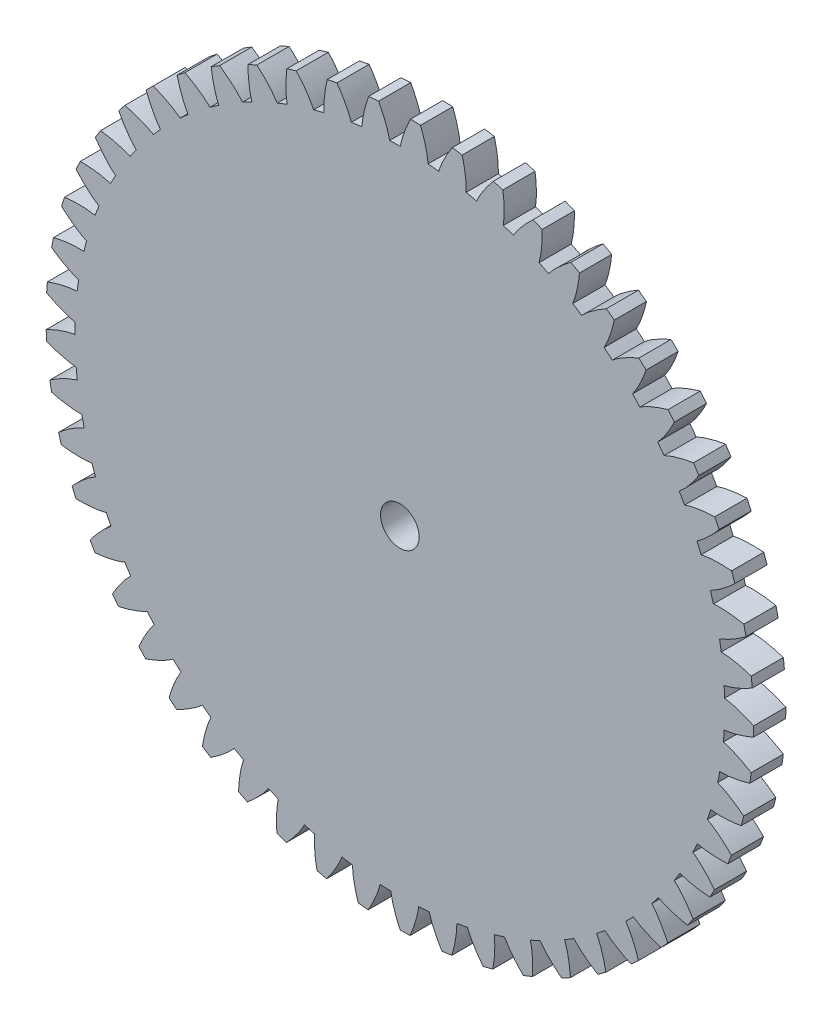
SolidWorks part; units mm, degrees
ref_plane "前视基准面" through (0, 0, 0) normal (0, 0, 1) x (1, 0, 0)
ref_plane "上视基准面" through (0, 0, 0) normal (0, 1, 0) x (1, 0, 0)
ref_plane "右视基准面" through (0, 0, 0) normal (1, 0, 0) x (0, 0, -1)
other "Configuration Table"
sketch "草图1" plane through (0, 0, 0) normal (0, 0, 1) x (1, 0, 0)
  line L0 (0, -0.6254) -> (0.7899, 52.9941) construction
  line L1 (0, 0) -> (2.4394, 54.9459) construction
  line L2 (0, 0) -> (5.6902, 54.7049) construction
  circle A1 centre (0, 0) radius 50.5
  circle A2 centre (0, 0) radius 55
  circle A3 centre (0, 0) radius 53
  spline S0 degree 4 poles (0, 49.8037) (0.0009, 49.8441) (0.0062, 49.9572) (0.0271, 50.1706) (0.0767, 50.5172) (0.2017, 51.1568) (0.406, 51.9145) (0.6892, 52.7572) (1.0452, 53.6472) (1.3816, 54.3975) (1.7458, 55.1347) (2.1353, 55.8588) (2.636, 56.7216) (3.2802, 57.738) (4.0884, 58.8925) (5.0797, 60.1668) (6.1512, 61.415) (7.277, 62.6131) (8.307, 63.6193) (9.2162, 64.4504) (9.9947, 65.1248) (10.6222, 65.6491) (11.4311, 66.297) (12.2339, 66.9127) (13.0864, 67.5292) (14.0681, 68.2126) (14.984, 68.8118) (15.7557, 69.3016) (16.7458, 69.8914) (17.2547, 70.186) (17.9782, 70.5929) (18.5198, 70.8852) (19.0141, 71.1478) (19.2931, 71.2903) (19.4555, 71.3741) knots 0 0 0 0 0 0.005377 0.015084 0.028532 0.04661 0.092111 0.119476 0.146842 0.174209 0.201575 0.228941 0.256307 0.307035 0.361767 0.4165 0.471232 0.525964 0.580697 0.608063 0.635429 0.662795 0.690161 0.744894 0.77226 0.799626 0.854358 0.881725 0.909091 0.931818 0.954545 0.977273 1 1 1 1 1 construction
  spline S1 degree 4 poles (0.0782, 50.4999) (0.0847, 50.5384) (0.1149, 50.7105) (0.2179, 51.2167) (0.406, 51.9145) (0.6892, 52.7572) (1.067, 53.7016) (1.3456, 54.3168) (1.5514, 54.739) (1.6707, 54.9746) knots 0.023342 0.023342 0.023342 0.023342 0.023342 0.028532 0.04661 0.092111 0.119476 0.146842 0.182011 0.182011 0.182011 0.182011 0.182011
  spline S2 degree 4 poles (4.3974, 50.3082) (4.3943, 50.347) (4.3795, 50.5211) (4.3218, 51.0345) (4.1963, 51.7462) (3.9888, 52.6107) (3.6962, 53.5849) (3.4732, 54.2223) (3.3057, 54.6611) (3.2077, 54.9064) knots 0.023342 0.023342 0.023342 0.023342 0.023342 0.028532 0.04661 0.092111 0.119476 0.146842 0.182011 0.182011 0.182011 0.182011 0.182011
  spline S3 degree 4 poles (6.0504, 50.1362) (6.0614, 50.1736) (6.1118, 50.3409) (6.2739, 50.8315) (6.5432, 51.5021) (6.9242, 52.3054) (7.411, 53.1985) (7.7604, 53.7764) (8.0147, 54.1713) (8.161, 54.3912) knots 0.023342 0.023342 0.023342 0.023342 0.023342 0.028532 0.04661 0.092111 0.119476 0.146842 0.182011 0.182011 0.182011 0.182011 0.182011
  dimension "D1" = 106
  dimension "D2" = 101
  dimension "D3" = 110
  dimension "D4" = 1.698
  dimension "D5" = 5.094
sketch "草图2" plane through (0, 0, 0) normal (0, 0, 1) x (1, 0, 0)
  circle A0 centre (0, 0) radius 50.5 construction
  circle A1 centre (0, 0) radius 55 construction
  arc A2 (6.0504, 50.1362) -> (4.3974, 50.3082) centre (0, 0) ccw
  arc A3 (3.2077, 54.9064) -> (1.6707, 54.9746) centre (0, 0) ccw
  arc A4 (9.6792, 54.1416) -> (8.161, 54.3912) centre (0, 0) ccw
  arc A5 (11.9377, 49.0687) -> (10.3166, 49.435) centre (0, 0) ccw
  arc A6 (16.0147, 52.6168) -> (14.5367, 53.0442) centre (0, 0) ccw
  arc A7 (17.6575, 47.3124) -> (16.0911, 47.8678) centre (0, 0) ccw
  arc A8 (22.1255, 50.3534) -> (20.7084, 50.9526) centre (0, 0) ccw
  arc A9 (23.1293, 44.8919) -> (21.6396, 45.6287) centre (0, 0) ccw
  arc A10 (27.9256, 47.3831) -> (26.5894, 48.1457) centre (0, 0) ccw
  arc A11 (28.2765, 41.8412) -> (26.8844, 42.749) centre (0, 0) ccw
  arc A12 (33.3338, 43.7477) -> (32.0971, 44.6629) centre (0, 0) ccw
  arc A13 (33.0267, 38.2032) -> (31.7517, 39.2693) centre (0, 0) ccw
  arc A14 (38.274, 39.4981) -> (37.1542, 40.5532) centre (0, 0) ccw
  arc A15 (37.3133, 34.0289) -> (36.1734, 35.2383) centre (0, 0) ccw
  arc A16 (42.6769, 34.6941) -> (41.6898, 35.8742) centre (0, 0) ccw
  arc A17 (41.0761, 29.3769) -> (40.0872, 30.7126) centre (0, 0) ccw
  arc A18 (46.4808, 29.4031) -> (45.6401, 30.6917) centre (0, 0) ccw
  arc A19 (44.2623, 24.3125) -> (43.4383, 25.7558) centre (0, 0) ccw
  arc A20 (49.6321, 23.6992) -> (48.9498, 25.0782) centre (0, 0) ccw
  arc A21 (46.8272, 18.9068) -> (46.1797, 20.4374) centre (0, 0) ccw
  arc A22 (52.0867, 17.6628) -> (51.5723, 19.1128) centre (0, 0) ccw
  arc A23 (48.7347, 13.2357) -> (48.2727, 14.8322) centre (0, 0) ccw
  arc A24 (53.8102, 11.3783) -> (53.4708, 12.879) centre (0, 0) ccw
  arc A25 (49.958, 7.3788) -> (49.6882, 9.0187) centre (0, 0) ccw
  arc A26 (54.7782, 4.9342) -> (54.6188, 6.4644) centre (0, 0) ccw
  arc A27 (50.4801, 1.4183) -> (50.4061, 3.0786) centre (0, 0) ccw
  arc A28 (54.9773, -1.5793) -> (55, -0.0409) centre (0, 0) ccw
  arc A29 (50.2935, -4.5621) -> (50.4164, -2.9047) centre (0, 0) ccw
  arc A30 (54.4047, -8.0705) -> (54.6091, -6.5456) centre (0, 0) ccw
  arc A31 (49.4009, -10.4784) -> (49.719, -8.8472) centre (0, 0) ccw
  arc A32 (53.0683, -14.4485) -> (53.4516, -12.9585) centre (0, 0) ccw
  arc A33 (47.8149, -16.2477) -> (48.3236, -14.6655) centre (0, 0) ccw
  arc A34 (50.9869, -20.6236) -> (51.5438, -19.1894) centre (0, 0) ccw
  arc A35 (45.5576, -21.7889) -> (46.2499, -20.278) centre (0, 0) ccw
  arc A36 (48.1898, -26.5093) -> (48.9125, -25.151) centre (0, 0) ccw
  arc A37 (42.6608, -27.0242) -> (43.5269, -25.6058) centre (0, 0) ccw
  arc A38 (44.7163, -32.0228) -> (45.5945, -30.7595) centre (0, 0) ccw
  arc A39 (39.1651, -31.8801) -> (40.193, -30.5741) centre (0, 0) ccw
  arc A40 (40.615, -37.0867) -> (41.6364, -35.9362) centre (0, 0) ccw
  arc A41 (35.1197, -36.2885) -> (36.2948, -35.1133) centre (0, 0) ccw
  arc A42 (35.9435, -41.6301) -> (37.0939, -40.6084) centre (0, 0) ccw
  arc A43 (30.5812, -40.1876) -> (31.887, -39.1595) centre (0, 0) ccw
  arc A44 (30.7675, -45.589) -> (32.0307, -44.7106) centre (0, 0) ccw
  arc A45 (25.6135, -43.5224) -> (27.0317, -42.656) centre (0, 0) ccw
  arc A46 (25.1596, -48.908) -> (26.5178, -48.1851) centre (0, 0) ccw
  arc A47 (20.2861, -46.2463) -> (21.7969, -45.5538) centre (0, 0) ccw
  arc A48 (19.1985, -51.5404) -> (20.6326, -50.9833) centre (0, 0) ccw
  arc A49 (14.6741, -48.321) -> (16.2561, -47.812) centre (0, 0) ccw
  arc A50 (12.9679, -53.4494) -> (14.4579, -53.0657) centre (0, 0) ccw
  arc A51 (8.856, -49.7174) -> (10.4872, -49.3991) centre (0, 0) ccw
  arc A52 (6.5553, -54.608) -> (8.0801, -54.4032) centre (0, 0) ccw
  arc A53 (2.9136, -50.4159) -> (4.571, -50.2927) centre (0, 0) ccw
  arc A54 (0.0506, -55) -> (1.589, -54.977) centre (0, 0) ccw
  arc A55 (-3.0697, -50.4066) -> (-1.4094, -50.4803) centre (0, 0) ccw
  arc A56 (-6.4548, -54.6199) -> (-4.9245, -54.7791) centre (0, 0) ccw
  arc A57 (-9.0099, -49.6898) -> (-7.37, -49.9593) centre (0, 0) ccw
  arc A58 (-12.8696, -53.4731) -> (-11.3688, -53.8122) centre (0, 0) ccw
  arc A59 (-14.8236, -48.2754) -> (-13.2271, -48.737) centre (0, 0) ccw
  arc A60 (-19.1037, -51.5757) -> (-17.6536, -52.0898) centre (0, 0) ccw
  arc A61 (-20.4293, -46.1833) -> (-18.8985, -46.8305) centre (0, 0) ccw
  arc A62 (-25.0696, -48.9542) -> (-23.6905, -49.6363) centre (0, 0) ccw
  arc A63 (-25.7481, -43.4429) -> (-24.3047, -44.2666) centre (0, 0) ccw
  arc A64 (-30.6836, -45.6456) -> (-29.3948, -46.4859) centre (0, 0) ccw
  arc A65 (-30.7055, -40.0926) -> (-29.3696, -41.0813) centre (0, 0) ccw
  arc A66 (-35.8669, -41.6961) -> (-34.6866, -42.683) centre (0, 0) ccw
  arc A67 (-35.2319, -36.1796) -> (-34.0223, -37.3193) centre (0, 0) ccw
  arc A68 (-40.5467, -37.1614) -> (-39.4914, -38.281) centre (0, 0) ccw
  arc A69 (-39.2637, -31.7587) -> (-38.1974, -33.0335) centre (0, 0) ccw
  arc A70 (-44.6573, -32.105) -> (-43.7418, -33.3415) centre (0, 0) ccw
  arc A71 (-42.7443, -26.8919) -> (-41.8363, -28.2839) centre (0, 0) ccw
  arc A72 (-48.141, -26.5979) -> (-47.3782, -27.934) centre (0, 0) ccw
  arc A73 (-45.6249, -21.6477) -> (-44.8878, -23.1373) centre (0, 0) ccw
  arc A74 (-50.9489, -20.7174) -> (-50.3495, -22.1344) centre (0, 0) ccw
  arc A75 (-47.865, -16.0995) -> (-47.3093, -17.6658) centre (0, 0) ccw
  arc A76 (-53.0416, -14.5461) -> (-52.614, -16.024) centre (0, 0) ccw
  arc A77 (-49.4332, -10.3254) -> (-49.0666, -11.9464) centre (0, 0) ccw
  arc A78 (-54.3897, -8.1706) -> (-54.1399, -9.6887) centre (0, 0) ccw
  arc A79 (-50.3074, -4.4063) -> (-50.1352, -6.0593) centre (0, 0) ccw
  arc A80 (-54.9743, -1.6804) -> (-54.9058, -3.2174) centre (0, 0) ccw
  arc A81 (-50.4754, 1.5747) -> (-50.4999, -0.0871) centre (0, 0) ccw
  arc A82 (-54.7872, 4.8334) -> (-54.901, 3.299) centre (0, 0) ccw
  arc A83 (-49.9349, 7.5335) -> (-50.1558, 5.8863) centre (0, 0) ccw
  arc A84 (-53.831, 11.2793) -> (-54.1254, 9.7692) centre (0, 0) ccw
  arc A85 (-48.6934, 13.3866) -> (-49.1075, 11.777) centre (0, 0) ccw
  arc A86 (-52.1191, 17.5669) -> (-52.5901, 16.1022) centre (0, 0) ccw
  arc A87 (-46.7684, 19.0517) -> (-47.37, 17.5025) centre (0, 0) ccw
  arc A88 (-49.6756, 23.6079) -> (-50.3165, 22.2092) centre (0, 0) ccw
  arc A89 (-44.1868, 24.4495) -> (-44.9674, 22.9822) centre (0, 0) ccw
  arc A90 (-46.5348, 29.3175) -> (-47.3366, 28.0044) centre (0, 0) ccw
  arc A91 (-40.9849, 29.504) -> (-41.9336, 28.1394) centre (0, 0) ccw
  arc A92 (-42.7407, 34.6155) -> (-43.6922, 33.4065) centre (0, 0) ccw
  arc A93 (-37.2077, 34.1443) -> (-38.3111, 32.9015) centre (0, 0) ccw
  arc A94 (-38.3466, 39.4276) -> (-39.4344, 38.3396) centre (0, 0) ccw
  arc A95 (-32.9082, 38.3053) -> (-34.1509, 37.2017) centre (0, 0) ccw
  arc A96 (-33.4142, 43.6863) -> (-34.6231, 42.7346) centre (0, 0) ccw
  arc A97 (-28.1468, 41.9286) -> (-29.5112, 40.9797) centre (0, 0) ccw
  arc A98 (-28.0128, 47.3317) -> (-29.3257, 46.5296) centre (0, 0) ccw
  arc A99 (-22.9902, 44.9633) -> (-24.4573, 44.1825) centre (0, 0) ccw
  arc A100 (-22.2181, 50.3126) -> (-23.6167, 49.6714) centre (0, 0) ccw
  arc A101 (-17.5108, 47.3669) -> (-19.06, 46.765) centre (0, 0) ccw
  arc A102 (-16.1115, 52.5873) -> (-17.5761, 52.116) centre (0, 0) ccw
  arc A103 (-11.7857, 49.1055) -> (-13.3952, 48.6911) centre (0, 0) ccw
  arc A104 (-9.7788, 54.1237) -> (-11.2888, 53.829) centre (0, 0) ccw
  arc A105 (-5.8951, 50.1547) -> (-7.5423, 49.9336) centre (0, 0) ccw
  arc A106 (-3.3087, 54.9004) -> (-4.8431, 54.7864) centre (0, 0) ccw
  arc A107 (0.0782, 50.4999) -> (-1.5836, 50.4752) centre (0, 0) ccw
  spline S1 degree 4 poles (-2987.0139, 269.4484) (-118.9779, 32.2173) (-1.5624, 33.5542) (5.7155, 43.1306) (4.1963, 51.7462) (3.9888, 52.6107) (-3.1358, 76.3332) (-47.8281, 87.469) (81.7258, 73.9843) (-2995.7873, -8.3312) knots -1.04429 -1.04429 -1.04429 -1.04429 -1.04429 0.028532 0.04661 0.092111 0.119476 0.146842 3.343823 3.343823 3.343823 3.343823 3.343823 only from (4.3974, 50.3082) to (3.2077, 54.9064) construction
  spline S2 degree 4 poles (2999.1401, 3.6794) (121.3648, 21.5467) (4.5298, 33.2837) (-1.8708, 43.4674) (0.406, 51.9145) (0.6892, 52.7572) (9.8881, 75.755) (55.3914, 82.8863) (-74.8477, 80.9358) (2983.2621, -273.7849) knots -1.04429 -1.04429 -1.04429 -1.04429 -1.04429 0.028532 0.04661 0.092111 0.119476 0.146842 3.343823 3.343823 3.343823 3.343823 3.343823 only from (0.0782, 50.4999) to (1.6707, 54.9746) construction
  spline S3 degree 4 poles (6.0504, 50.1362) (6.0614, 50.1736) (6.1118, 50.3409) (6.2739, 50.8315) (6.5432, 51.5021) (6.9242, 52.3054) (7.411, 53.1985) (7.7604, 53.7764) (8.0147, 54.1713) (8.161, 54.3912) knots 0.023342 0.023342 0.023342 0.023342 0.023342 0.028532 0.04661 0.092111 0.119476 0.146842 0.182011 0.182011 0.182011 0.182011 0.182011
  spline S4 degree 4 poles (4.3974, 50.3082) (4.3943, 50.347) (4.3795, 50.5211) (4.3218, 51.0345) (4.1963, 51.7462) (3.9888, 52.6107) (3.6962, 53.5849) (3.4732, 54.2223) (3.3057, 54.6611) (3.2077, 54.9064) knots 0.023342 0.023342 0.023342 0.023342 0.023342 0.028532 0.04661 0.092111 0.119476 0.146842 0.182011 0.182011 0.182011 0.182011 0.182011
  spline S5 degree 4 poles (0.0782, 50.4999) (0.0847, 50.5384) (0.1149, 50.7105) (0.2179, 51.2167) (0.406, 51.9145) (0.6892, 52.7572) (1.067, 53.7016) (1.3456, 54.3168) (1.5514, 54.739) (1.6707, 54.9746) knots 0.023342 0.023342 0.023342 0.023342 0.023342 0.028532 0.04661 0.092111 0.119476 0.146842 0.182011 0.182011 0.182011 0.182011 0.182011
  spline S6 degree 4 poles (10.3166, 49.435) (10.3182, 49.4739) (10.324, 49.6486) (10.3275, 50.1651) (10.287, 50.8867) (10.1833, 51.7697) (10.008, 52.7716) (9.8619, 53.431) (9.7474, 53.8865) (9.6792, 54.1416) knots 0.023342 0.023342 0.023342 0.023342 0.023342 0.028532 0.04661 0.092111 0.119476 0.146842 0.182011 0.182011 0.182011 0.182011 0.182011
  spline S7 degree 4 poles (11.9377, 49.0687) (11.9531, 49.1046) (12.0229, 49.2647) (12.2419, 49.7326) (12.5886, 50.3667) (13.0619, 51.1193) (13.6509, 51.9486) (14.0663, 52.4811) (14.3654, 52.8431) (14.5367, 53.0442) knots 0.023342 0.023342 0.023342 0.023342 0.023342 0.028532 0.04661 0.092111 0.119476 0.146842 0.182011 0.182011 0.182011 0.182011 0.182011
  spline S8 degree 4 poles (16.0911, 47.8678) (16.0972, 47.9063) (16.1237, 48.079) (16.1882, 48.5916) (16.2334, 49.3129) (16.2347, 50.2019) (16.1792, 51.2175) (16.1121, 51.8895) (16.0523, 52.3554) (16.0147, 52.6168) knots 0.023342 0.023342 0.023342 0.023342 0.023342 0.028532 0.04661 0.092111 0.119476 0.146842 0.182011 0.182011 0.182011 0.182011 0.182011
  spline S9 degree 4 poles (17.6575, 47.3124) (17.6769, 47.3462) (17.7652, 47.497) (18.038, 47.9357) (18.4573, 48.5243) (19.0163, 49.2157) (19.6992, 49.9694) (20.1746, 50.4491) (20.5145, 50.7732) (20.7084, 50.9526) knots 0.023342 0.023342 0.023342 0.023342 0.023342 0.028532 0.04661 0.092111 0.119476 0.146842 0.182011 0.182011 0.182011 0.182011 0.182011
  spline S10 degree 4 poles (21.6396, 45.6287) (21.6503, 45.6662) (21.697, 45.8346) (21.8216, 46.3359) (21.9518, 47.0468) (22.0583, 47.9294) (22.1233, 48.9445) (22.1361, 49.6197) (22.1319, 50.0894) (22.1255, 50.3534) knots 0.023342 0.023342 0.023342 0.023342 0.023342 0.028532 0.04661 0.092111 0.119476 0.146842 0.182011 0.182011 0.182011 0.182011 0.182011
  spline S11 degree 4 poles (23.1293, 44.8919) (23.1527, 44.9231) (23.2581, 45.0624) (23.5809, 45.4658) (24.0668, 46.0007) (24.7037, 46.6211) (25.471, 47.2888) (25.9998, 47.7088) (26.3756, 47.9905) (26.5894, 48.1457) knots 0.023342 0.023342 0.023342 0.023342 0.023342 0.028532 0.04661 0.092111 0.119476 0.146842 0.182011 0.182011 0.182011 0.182011 0.182011
  spline S12 degree 4 poles (26.8844, 42.749) (26.8994, 42.785) (26.9657, 42.9467) (27.1488, 43.4298) (27.3621, 44.1202) (27.5723, 44.9841) (27.7568, 45.9844) (27.8495, 46.6533) (27.9008, 47.1202) (27.9256, 47.3831) knots 0.023342 0.023342 0.023342 0.023342 0.023342 0.028532 0.04661 0.092111 0.119476 0.146842 0.182011 0.182011 0.182011 0.182011 0.182011
  spline S13 degree 4 poles (28.2765, 41.8412) (28.3034, 41.8695) (28.4246, 41.9953) (28.7928, 42.3577) (29.3386, 42.8314) (30.0443, 43.3721) (30.8852, 43.9444) (31.46, 44.2989) (31.8665, 44.5341) (32.0971, 44.6629) knots 0.023342 0.023342 0.023342 0.023342 0.023342 0.028532 0.04661 0.092111 0.119476 0.146842 0.182011 0.182011 0.182011 0.182011 0.182011
  spline S14 degree 4 poles (31.7517, 39.2693) (31.7709, 39.3032) (31.8558, 39.4559) (32.0948, 39.914) (32.3883, 40.5744) (32.6992, 41.4073) (33.0007, 42.3787) (33.1718, 43.032) (33.278, 43.4895) (33.3338, 43.7477) knots 0.023342 0.023342 0.023342 0.023342 0.023342 0.028532 0.04661 0.092111 0.119476 0.146842 0.182011 0.182011 0.182011 0.182011 0.182011
  spline S15 degree 4 poles (33.0267, 38.2032) (33.0567, 38.2281) (33.192, 38.3387) (33.6005, 38.655) (34.1984, 39.0608) (34.9632, 39.5142) (35.8659, 39.983) (36.4785, 40.2671) (36.91, 40.4526) (37.1542, 40.5532) knots 0.023342 0.023342 0.023342 0.023342 0.023342 0.028532 0.04661 0.092111 0.119476 0.146842 0.182011 0.182011 0.182011 0.182011 0.182011
  spline S16 degree 4 poles (36.1734, 35.2383) (36.1964, 35.2697) (36.2988, 35.4113) (36.5903, 35.8379) (36.9598, 36.4589) (37.367, 37.2492) (37.7813, 38.1782) (38.0285, 38.8066) (38.188, 39.2484) (38.274, 39.4981) knots 0.023342 0.023342 0.023342 0.023342 0.023342 0.028532 0.04661 0.092111 0.119476 0.146842 0.182011 0.182011 0.182011 0.182011 0.182011
  spline S17 degree 4 poles (37.3133, 34.0289) (37.3461, 34.05) (37.4934, 34.1439) (37.9365, 34.4096) (38.5783, 34.7419) (39.3913, 35.1017) (40.343, 35.4604) (40.985, 35.67) (41.4354, 35.8032) (41.6898, 35.8742) knots 0.023342 0.023342 0.023342 0.023342 0.023342 0.028532 0.04661 0.092111 0.119476 0.146842 0.182011 0.182011 0.182011 0.182011 0.182011
  spline S18 degree 4 poles (40.0872, 30.7126) (40.1138, 30.7411) (40.2322, 30.8696) (40.5721, 31.2587) (41.0125, 31.8316) (41.5103, 32.5683) (42.0316, 33.4417) (42.3514, 34.0365) (42.562, 34.4563) (42.6769, 34.6941) knots 0.023342 0.023342 0.023342 0.023342 0.023342 0.028532 0.04661 0.092111 0.119476 0.146842 0.182011 0.182011 0.182011 0.182011 0.182011
  spline S19 degree 4 poles (41.0761, 29.3769) (41.1111, 29.394) (41.2686, 29.4698) (41.7399, 29.6813) (42.4165, 29.9352) (43.2664, 30.1964) (44.2539, 30.44) (44.9162, 30.5722) (45.3792, 30.6512) (45.6401, 30.6917) knots 0.023342 0.023342 0.023342 0.023342 0.023342 0.028532 0.04661 0.092111 0.119476 0.146842 0.182011 0.182011 0.182011 0.182011 0.182011
  spline S20 degree 4 poles (43.4383, 25.7558) (43.4681, 25.7809) (43.6009, 25.8945) (43.9844, 26.2407) (44.4895, 26.7575) (45.0709, 27.4301) (45.6919, 28.2357) (46.0797, 28.7886) (46.3386, 29.1805) (46.4808, 29.4031) knots 0.023342 0.023342 0.023342 0.023342 0.023342 0.028532 0.04661 0.092111 0.119476 0.146842 0.182011 0.182011 0.182011 0.182011 0.182011
  spline S21 degree 4 poles (44.2623, 24.3125) (44.2991, 24.3253) (44.4644, 24.382) (44.9575, 24.5362) (45.6593, 24.7084) (46.5341, 24.8672) (47.5435, 24.9923) (48.2168, 25.0453) (48.6859, 25.0689) (48.9498, 25.0782) knots 0.023342 0.023342 0.023342 0.023342 0.023342 0.028532 0.04661 0.092111 0.119476 0.146842 0.182011 0.182011 0.182011 0.182011 0.182011
  spline S22 degree 4 poles (46.1797, 20.4374) (46.2122, 20.4589) (46.3575, 20.5559) (46.7792, 20.8543) (47.3419, 21.3078) (47.9988, 21.9069) (48.7107, 22.6334) (49.1612, 23.1365) (49.4646, 23.4951) (49.6321, 23.6992) knots 0.023342 0.023342 0.023342 0.023342 0.023342 0.028532 0.04661 0.092111 0.119476 0.146842 0.182011 0.182011 0.182011 0.182011 0.182011
  spline S23 degree 4 poles (46.8272, 18.9068) (46.8652, 18.9152) (47.0361, 18.9519) (47.5439, 19.0467) (48.2612, 19.1347) (49.1486, 19.1889) (50.1657, 19.1938) (50.8405, 19.1667) (51.3091, 19.1347) (51.5723, 19.1128) knots 0.023342 0.023342 0.023342 0.023342 0.023342 0.028532 0.04661 0.092111 0.119476 0.146842 0.182011 0.182011 0.182011 0.182011 0.182011
  spline S24 degree 4 poles (48.2727, 14.8322) (48.3076, 14.8496) (48.4633, 14.9288) (48.9174, 15.1752) (49.5298, 15.559) (50.2529, 16.0762) (51.0457, 16.7134) (51.5526, 17.1597) (51.8962, 17.4798) (52.0867, 17.6628) knots 0.023342 0.023342 0.023342 0.023342 0.023342 0.028532 0.04661 0.092111 0.119476 0.146842 0.182011 0.182011 0.182011 0.182011 0.182011
  spline S25 degree 4 poles (48.7347, 13.2357) (48.7734, 13.2396) (48.9474, 13.2558) (49.4629, 13.2899) (50.1856, 13.2924) (51.0732, 13.2413) (52.0837, 13.1258) (52.7506, 13.0191) (53.2121, 12.9319) (53.4708, 12.879) knots 0.023342 0.023342 0.023342 0.023342 0.023342 0.028532 0.04661 0.092111 0.119476 0.146842 0.182011 0.182011 0.182011 0.182011 0.182011
  spline S26 degree 4 poles (49.6882, 9.0187) (49.7248, 9.0319) (49.8889, 9.0921) (50.3689, 9.2831) (51.0223, 9.5917) (51.8016, 10.0198) (52.6642, 10.5588) (53.2203, 10.9419) (53.5994, 11.2192) (53.8102, 11.3783) knots 0.023342 0.023342 0.023342 0.023342 0.023342 0.028532 0.04661 0.092111 0.119476 0.146842 0.182011 0.182011 0.182011 0.182011 0.182011
  spline S27 degree 4 poles (49.958, 7.3788) (49.997, 7.378) (50.1717, 7.3736) (50.6876, 7.3465) (51.4055, 7.2635) (52.2808, 7.1077) (53.2706, 6.8736) (53.9202, 6.6888) (54.3681, 6.5476) (54.6188, 6.4644) knots 0.023342 0.023342 0.023342 0.023342 0.023342 0.028532 0.04661 0.092111 0.119476 0.146842 0.182011 0.182011 0.182011 0.182011 0.182011
  spline S28 degree 4 poles (50.4061, 3.0786) (50.444, 3.0874) (50.614, 3.1278) (51.1133, 3.2606) (51.7986, 3.4898) (52.6231, 3.8227) (53.5433, 4.2559) (54.1409, 4.5706) (54.5501, 4.8011) (54.7782, 4.9342) knots 0.023342 0.023342 0.023342 0.023342 0.023342 0.028532 0.04661 0.092111 0.119476 0.146842 0.182011 0.182011 0.182011 0.182011 0.182011
  spline S29 degree 4 poles (50.4801, 1.4183) (50.5187, 1.413) (50.6916, 1.3878) (51.2007, 1.2999) (51.9037, 1.1326) (52.7545, 0.8744) (53.7097, 0.5248) (54.3328, 0.2645) (54.7609, 0.0714) (55, -0.0409) knots 0.023342 0.023342 0.023342 0.023342 0.023342 0.028532 0.04661 0.092111 0.119476 0.146842 0.182011 0.182011 0.182011 0.182011 0.182011
  spline S30 degree 4 poles (50.4164, -2.9047) (50.4551, -2.9005) (50.6287, -2.8804) (51.1402, -2.8076) (51.8478, -2.661) (52.7058, -2.428) (53.6709, -2.1067) (54.3014, -1.8649) (54.7351, -1.6844) (54.9773, -1.5793) knots 0.023342 0.023342 0.023342 0.023342 0.023342 0.028532 0.04661 0.092111 0.119476 0.146842 0.182011 0.182011 0.182011 0.182011 0.182011
  spline S31 degree 4 poles (50.2935, -4.5621) (50.3312, -4.572) (50.4999, -4.6174) (50.995, -4.7649) (51.6734, -5.0142) (52.4876, -5.3711) (53.3947, -5.8313) (53.9827, -6.1634) (54.385, -6.4059) (54.6091, -6.5456) knots 0.023342 0.023342 0.023342 0.023342 0.023342 0.028532 0.04661 0.092111 0.119476 0.146842 0.182011 0.182011 0.182011 0.182011 0.182011
  spline S32 degree 4 poles (49.719, -8.8472) (49.758, -8.8476) (49.9327, -8.8483) (50.4492, -8.8364) (51.1692, -8.7746) (52.0487, -8.6447) (53.045, -8.4398) (53.6997, -8.2742) (54.1517, -8.1463) (54.4047, -8.0705) knots 0.023342 0.023342 0.023342 0.023342 0.023342 0.028532 0.04661 0.092111 0.119476 0.146842 0.182011 0.182011 0.182011 0.182011 0.182011
  spline S33 degree 4 poles (49.4009, -10.4784) (49.4372, -10.4927) (49.5994, -10.5577) (50.0736, -10.7628) (50.7176, -11.0905) (51.4839, -11.5413) (52.3303, -12.1055) (52.8749, -12.5049) (53.2456, -12.7932) (53.4516, -12.9585) knots 0.023342 0.023342 0.023342 0.023342 0.023342 0.028532 0.04661 0.092111 0.119476 0.146842 0.182011 0.182011 0.182011 0.182011 0.182011
  spline S34 degree 4 poles (48.3236, -14.6655) (48.3623, -14.6705) (48.5357, -14.6918) (49.05, -14.7411) (49.7722, -14.7649) (50.661, -14.74) (51.6745, -14.6543) (52.3442, -14.5674) (52.8081, -14.4938) (53.0683, -14.4485) knots 0.023342 0.023342 0.023342 0.023342 0.023342 0.028532 0.04661 0.092111 0.119476 0.146842 0.182011 0.182011 0.182011 0.182011 0.182011
  spline S35 degree 4 poles (47.8149, -16.2477) (47.8492, -16.2662) (48.0026, -16.3499) (48.4492, -16.6096) (49.0499, -17.0112) (49.7576, -17.5495) (50.5312, -18.2098) (51.0248, -18.6708) (51.3588, -19.0009) (51.5438, -19.1894) knots 0.023342 0.023342 0.023342 0.023342 0.023342 0.028532 0.04661 0.092111 0.119476 0.146842 0.182011 0.182011 0.182011 0.182011 0.182011
  spline S36 degree 4 poles (46.2499, -20.278) (46.2877, -20.2875) (46.4574, -20.3292) (46.9622, -20.439) (47.6766, -20.548) (48.562, -20.6283) (49.5786, -20.6632) (50.2539, -20.656) (50.7232, -20.6378) (50.9869, -20.6236) knots 0.023342 0.023342 0.023342 0.023342 0.023342 0.028532 0.04661 0.092111 0.119476 0.146842 0.182011 0.182011 0.182011 0.182011 0.182011
  spline S37 degree 4 poles (45.5576, -21.7889) (45.5895, -21.8113) (45.7319, -21.9126) (46.1446, -22.2232) (46.6937, -22.6931) (47.3327, -23.3113) (48.0228, -24.0585) (48.4584, -24.5746) (48.751, -24.9419) (48.9125, -25.151) knots 0.023342 0.023342 0.023342 0.023342 0.023342 0.028532 0.04661 0.092111 0.119476 0.146842 0.182011 0.182011 0.182011 0.182011 0.182011
  spline S38 degree 4 poles (43.5269, -25.6058) (43.5633, -25.6197) (43.7269, -25.6812) (44.2152, -25.8499) (44.9117, -26.0426) (45.7814, -26.2271) (46.7867, -26.382) (47.4581, -26.4547) (47.9263, -26.4922) (48.1898, -26.5093) knots 0.023342 0.023342 0.023342 0.023342 0.023342 0.028532 0.04661 0.092111 0.119476 0.146842 0.182011 0.182011 0.182011 0.182011 0.182011
  spline S39 degree 4 poles (42.6608, -27.0242) (42.6898, -27.0502) (42.8192, -27.1676) (43.1923, -27.5249) (43.682, -28.0564) (44.2434, -28.7459) (44.8403, -29.5694) (45.2117, -30.1334) (45.4589, -30.5328) (45.5945, -30.7595) knots 0.023342 0.023342 0.023342 0.023342 0.023342 0.028532 0.04661 0.092111 0.119476 0.146842 0.182011 0.182011 0.182011 0.182011 0.182011
  spline S40 degree 4 poles (40.193, -30.5741) (40.2275, -30.5923) (40.3826, -30.6726) (40.8475, -30.8979) (41.5163, -31.1717) (42.3581, -31.4578) (43.338, -31.7304) (43.9961, -31.8821) (44.4566, -31.9746) (44.7163, -32.0228) knots 0.023342 0.023342 0.023342 0.023342 0.023342 0.028532 0.04661 0.092111 0.119476 0.146842 0.182011 0.182011 0.182011 0.182011 0.182011
  spline S41 degree 4 poles (39.1651, -31.8801) (39.1909, -31.9094) (39.3055, -32.0413) (39.6337, -32.4402) (40.057, -33.0259) (40.533, -33.7769) (41.0283, -34.6653) (41.3304, -35.2693) (41.5286, -35.6951) (41.6364, -35.9362) knots 0.023342 0.023342 0.023342 0.023342 0.023342 0.028532 0.04661 0.092111 0.119476 0.146842 0.182011 0.182011 0.182011 0.182011 0.182011
  spline S42 degree 4 poles (36.2948, -35.1133) (36.3269, -35.1354) (36.4714, -35.2335) (36.9064, -35.5122) (37.5381, -35.8632) (38.3402, -36.2468) (39.281, -36.6334) (39.9165, -36.8618) (40.3628, -37.0082) (40.615, -37.0867) knots 0.023342 0.023342 0.023342 0.023342 0.023342 0.028532 0.04661 0.092111 0.119476 0.146842 0.182011 0.182011 0.182011 0.182011 0.182011
  spline S43 degree 4 poles (35.1197, -36.2885) (35.1418, -36.3206) (35.24, -36.4652) (35.5187, -36.9001) (35.8698, -37.5318) (36.2536, -38.3338) (36.6403, -39.2745) (36.8689, -39.91) (37.0153, -40.3563) (37.0939, -40.6084) knots 0.023342 0.023342 0.023342 0.023342 0.023342 0.028532 0.04661 0.092111 0.119476 0.146842 0.182011 0.182011 0.182011 0.182011 0.182011
  spline S44 degree 4 poles (31.887, -39.1595) (31.9163, -39.1852) (32.0482, -39.2998) (32.4472, -39.628) (33.033, -40.0512) (33.784, -40.527) (34.6725, -41.0222) (35.2766, -41.3242) (35.7024, -41.5223) (35.9435, -41.6301) knots 0.023342 0.023342 0.023342 0.023342 0.023342 0.028532 0.04661 0.092111 0.119476 0.146842 0.182011 0.182011 0.182011 0.182011 0.182011
  spline S45 degree 4 poles (30.5812, -40.1876) (30.5994, -40.222) (30.6798, -40.3772) (30.9051, -40.842) (31.179, -41.5108) (31.4652, -42.3525) (31.7381, -43.3324) (31.8898, -43.9905) (31.9825, -44.4509) (32.0307, -44.7106) knots 0.023342 0.023342 0.023342 0.023342 0.023342 0.028532 0.04661 0.092111 0.119476 0.146842 0.182011 0.182011 0.182011 0.182011 0.182011
  spline S46 degree 4 poles (27.0317, -42.656) (27.0577, -42.685) (27.1752, -42.8144) (27.5326, -43.1875) (28.0642, -43.677) (28.7537, -44.2383) (29.5773, -44.8351) (30.1414, -45.2064) (30.5409, -45.4535) (30.7675, -45.589) knots 0.023342 0.023342 0.023342 0.023342 0.023342 0.028532 0.04661 0.092111 0.119476 0.146842 0.182011 0.182011 0.182011 0.182011 0.182011
  spline S47 degree 4 poles (25.6135, -43.5224) (25.6274, -43.5588) (25.6889, -43.7224) (25.8577, -44.2106) (26.0506, -44.9071) (26.2352, -45.7768) (26.3902, -46.782) (26.4631, -47.4534) (26.5006, -47.9216) (26.5178, -48.1851) knots 0.023342 0.023342 0.023342 0.023342 0.023342 0.028532 0.04661 0.092111 0.119476 0.146842 0.182011 0.182011 0.182011 0.182011 0.182011
  spline S48 degree 4 poles (21.7969, -45.5538) (21.8193, -45.5856) (21.9206, -45.728) (22.2314, -46.1407) (22.7014, -46.6897) (23.3196, -47.3286) (24.067, -48.0186) (24.5832, -48.454) (24.9506, -48.7466) (25.1596, -48.908) knots 0.023342 0.023342 0.023342 0.023342 0.023342 0.028532 0.04661 0.092111 0.119476 0.146842 0.182011 0.182011 0.182011 0.182011 0.182011
  spline S49 degree 4 poles (20.2861, -46.2463) (20.2957, -46.2841) (20.3374, -46.4538) (20.4473, -46.9586) (20.5564, -47.673) (20.6369, -48.5584) (20.6719, -49.5749) (20.6649, -50.2502) (20.6468, -50.7196) (20.6326, -50.9833) knots 0.023342 0.023342 0.023342 0.023342 0.023342 0.028532 0.04661 0.092111 0.119476 0.146842 0.182011 0.182011 0.182011 0.182011 0.182011
  spline S50 degree 4 poles (16.2561, -47.812) (16.2746, -47.8463) (16.3584, -47.9997) (16.6181, -48.4462) (17.0199, -49.0469) (17.5583, -49.7545) (18.2187, -50.528) (18.6798, -51.0215) (19.01, -51.3555) (19.1985, -51.5404) knots 0.023342 0.023342 0.023342 0.023342 0.023342 0.028532 0.04661 0.092111 0.119476 0.146842 0.182011 0.182011 0.182011 0.182011 0.182011
  spline S51 degree 4 poles (14.6741, -48.321) (14.6791, -48.3597) (14.7004, -48.5331) (14.7498, -49.0473) (14.7737, -49.7696) (14.7489, -50.6584) (14.6635, -51.6719) (14.5766, -52.3416) (14.5031, -52.8055) (14.4579, -53.0657) knots 0.023342 0.023342 0.023342 0.023342 0.023342 0.028532 0.04661 0.092111 0.119476 0.146842 0.182011 0.182011 0.182011 0.182011 0.182011
  spline S52 degree 4 poles (10.4872, -49.3991) (10.5014, -49.4353) (10.5665, -49.5975) (10.7716, -50.0717) (11.0995, -50.7157) (11.5504, -51.4819) (12.1147, -52.3282) (12.5142, -52.8727) (12.8026, -53.2434) (12.9679, -53.4494) knots 0.023342 0.023342 0.023342 0.023342 0.023342 0.028532 0.04661 0.092111 0.119476 0.146842 0.182011 0.182011 0.182011 0.182011 0.182011
  spline S53 degree 4 poles (8.856, -49.7174) (8.8564, -49.7564) (8.8571, -49.9311) (8.8453, -50.4476) (8.7836, -51.1676) (8.6539, -52.0472) (8.4491, -53.0435) (8.2837, -53.6983) (8.1558, -54.1502) (8.0801, -54.4032) knots 0.023342 0.023342 0.023342 0.023342 0.023342 0.028532 0.04661 0.092111 0.119476 0.146842 0.182011 0.182011 0.182011 0.182011 0.182011
  spline S54 degree 4 poles (4.571, -50.2927) (4.5809, -50.3304) (4.6263, -50.4991) (4.7739, -50.9942) (5.0233, -51.6725) (5.3804, -52.4867) (5.8407, -53.3937) (6.173, -53.9816) (6.4155, -54.3839) (6.5553, -54.608) knots 0.023342 0.023342 0.023342 0.023342 0.023342 0.028532 0.04661 0.092111 0.119476 0.146842 0.182011 0.182011 0.182011 0.182011 0.182011
  spline S55 degree 4 poles (2.9136, -50.4159) (2.9094, -50.4546) (2.8894, -50.6282) (2.8166, -51.1397) (2.6702, -51.8474) (2.4373, -52.7054) (2.1162, -53.6705) (1.8745, -54.3011) (1.6941, -54.7348) (1.589, -54.977) knots 0.023342 0.023342 0.023342 0.023342 0.023342 0.028532 0.04661 0.092111 0.119476 0.146842 0.182011 0.182011 0.182011 0.182011 0.182011
  spline S56 degree 4 poles (-1.4094, -50.4803) (-1.404, -50.5189) (-1.3789, -50.6918) (-1.2909, -51.2009) (-1.1234, -51.9039) (-0.8651, -52.7546) (-0.5153, -53.7098) (-0.2549, -54.3329) (-0.0617, -54.7609) (0.0506, -55) knots 0.023342 0.023342 0.023342 0.023342 0.023342 0.028532 0.04661 0.092111 0.119476 0.146842 0.182011 0.182011 0.182011 0.182011 0.182011
  spline S57 degree 4 poles (-3.0697, -50.4066) (-3.0785, -50.4446) (-3.1188, -50.6146) (-3.2516, -51.1138) (-3.4807, -51.7993) (-3.8134, -52.6237) (-4.2464, -53.5441) (-4.561, -54.1417) (-4.7915, -54.5509) (-4.9245, -54.7791) knots 0.023342 0.023342 0.023342 0.023342 0.023342 0.028532 0.04661 0.092111 0.119476 0.146842 0.182011 0.182011 0.182011 0.182011 0.182011
  spline S58 degree 4 poles (-7.37, -49.9593) (-7.3692, -49.9983) (-7.3647, -50.173) (-7.3375, -50.6888) (-7.2544, -51.4067) (-7.0985, -52.282) (-6.8642, -53.2718) (-6.6793, -53.9213) (-6.538, -54.3693) (-6.4548, -54.6199) knots 0.023342 0.023342 0.023342 0.023342 0.023342 0.028532 0.04661 0.092111 0.119476 0.146842 0.182011 0.182011 0.182011 0.182011 0.182011
  spline S59 degree 4 poles (-9.0099, -49.6898) (-9.0231, -49.7264) (-9.0833, -49.8905) (-9.2742, -50.3705) (-9.5827, -51.024) (-10.0106, -51.8033) (-10.5495, -52.666) (-10.9325, -53.2222) (-11.2097, -53.6014) (-11.3688, -53.8122) knots 0.023342 0.023342 0.023342 0.023342 0.023342 0.028532 0.04661 0.092111 0.119476 0.146842 0.182011 0.182011 0.182011 0.182011 0.182011
  spline S60 degree 4 poles (-13.2271, -48.737) (-13.2309, -48.7758) (-13.2471, -48.9498) (-13.2811, -49.4652) (-13.2835, -50.1879) (-13.2322, -51.0755) (-13.1166, -52.0861) (-13.0098, -52.7529) (-12.9225, -53.2144) (-12.8696, -53.4731) knots 0.023342 0.023342 0.023342 0.023342 0.023342 0.028532 0.04661 0.092111 0.119476 0.146842 0.182011 0.182011 0.182011 0.182011 0.182011
  spline S61 degree 4 poles (-14.8236, -48.2754) (-14.8411, -48.3102) (-14.9203, -48.466) (-15.1666, -48.9201) (-15.5502, -49.5325) (-16.0673, -50.2558) (-16.7044, -51.0487) (-17.1506, -51.5556) (-17.4707, -51.8993) (-17.6536, -52.0898) knots 0.023342 0.023342 0.023342 0.023342 0.023342 0.028532 0.04661 0.092111 0.119476 0.146842 0.182011 0.182011 0.182011 0.182011 0.182011
  spline S62 degree 4 poles (-18.8985, -46.8305) (-18.9069, -46.8686) (-18.9436, -47.0394) (-19.0383, -47.5472) (-19.1262, -48.2646) (-19.1802, -49.152) (-19.1849, -50.1691) (-19.1578, -50.8439) (-19.1257, -51.3125) (-19.1037, -51.5757) knots 0.023342 0.023342 0.023342 0.023342 0.023342 0.028532 0.04661 0.092111 0.119476 0.146842 0.182011 0.182011 0.182011 0.182011 0.182011
  spline S63 degree 4 poles (-20.4293, -46.1833) (-20.4507, -46.2158) (-20.5478, -46.3611) (-20.8461, -46.7829) (-21.2995, -47.3457) (-21.8984, -48.0027) (-22.6248, -48.7147) (-23.1278, -49.1653) (-23.4863, -49.4687) (-23.6905, -49.6363) knots 0.023342 0.023342 0.023342 0.023342 0.023342 0.028532 0.04661 0.092111 0.119476 0.146842 0.182011 0.182011 0.182011 0.182011 0.182011
  spline S64 degree 4 poles (-24.3047, -44.2666) (-24.3175, -44.3034) (-24.3741, -44.4687) (-24.5283, -44.9618) (-24.7003, -45.6637) (-24.859, -46.5385) (-24.9839, -47.5479) (-25.0368, -48.2212) (-25.0603, -48.6903) (-25.0696, -48.9542) knots 0.023342 0.023342 0.023342 0.023342 0.023342 0.028532 0.04661 0.092111 0.119476 0.146842 0.182011 0.182011 0.182011 0.182011 0.182011
  spline S65 degree 4 poles (-25.7481, -43.4429) (-25.7733, -43.4727) (-25.8868, -43.6055) (-26.2329, -43.989) (-26.7497, -44.4942) (-27.4221, -45.0758) (-28.2277, -45.6968) (-28.7804, -46.0848) (-29.1723, -46.3437) (-29.3948, -46.4859) knots 0.023342 0.023342 0.023342 0.023342 0.023342 0.028532 0.04661 0.092111 0.119476 0.146842 0.182011 0.182011 0.182011 0.182011 0.182011
  spline S66 degree 4 poles (-29.3696, -41.0813) (-29.3867, -41.1163) (-29.4625, -41.2738) (-29.6739, -41.7452) (-29.9277, -42.4218) (-30.1887, -43.2717) (-30.4322, -44.2593) (-30.5643, -44.9216) (-30.6432, -45.3846) (-30.6836, -45.6456) knots 0.023342 0.023342 0.023342 0.023342 0.023342 0.028532 0.04661 0.092111 0.119476 0.146842 0.182011 0.182011 0.182011 0.182011 0.182011
  spline S67 degree 4 poles (-30.7055, -40.0926) (-30.734, -40.1192) (-30.8625, -40.2377) (-31.2515, -40.5776) (-31.8244, -41.0181) (-32.5609, -41.5161) (-33.4343, -42.0375) (-34.029, -42.3574) (-34.4488, -42.5681) (-34.6866, -42.683) knots 0.023342 0.023342 0.023342 0.023342 0.023342 0.028532 0.04661 0.092111 0.119476 0.146842 0.182011 0.182011 0.182011 0.182011 0.182011
  spline S68 degree 4 poles (-34.0223, -37.3193) (-34.0434, -37.3521) (-34.1373, -37.4995) (-34.4029, -37.9425) (-34.735, -38.5844) (-35.0947, -39.3975) (-35.4533, -40.3493) (-35.6628, -40.9913) (-35.7959, -41.4417) (-35.8669, -41.6961) knots 0.023342 0.023342 0.023342 0.023342 0.023342 0.028532 0.04661 0.092111 0.119476 0.146842 0.182011 0.182011 0.182011 0.182011 0.182011
  spline S69 degree 4 poles (-35.2319, -36.1796) (-35.2633, -36.2026) (-35.4049, -36.3051) (-35.8314, -36.5966) (-36.4524, -36.9662) (-37.2426, -37.3736) (-38.1715, -37.7881) (-38.7999, -38.0354) (-39.2416, -38.195) (-39.4914, -38.281) knots 0.023342 0.023342 0.023342 0.023342 0.023342 0.028532 0.04661 0.092111 0.119476 0.146842 0.182011 0.182011 0.182011 0.182011 0.182011
  spline S70 degree 4 poles (-38.1974, -33.0335) (-38.2222, -33.0635) (-38.3329, -33.1987) (-38.6491, -33.6073) (-39.0547, -34.2053) (-39.5081, -34.9702) (-39.9767, -35.8729) (-40.2607, -36.4857) (-40.4461, -36.9172) (-40.5467, -37.1614) knots 0.023342 0.023342 0.023342 0.023342 0.023342 0.028532 0.04661 0.092111 0.119476 0.146842 0.182011 0.182011 0.182011 0.182011 0.182011
  spline S71 degree 4 poles (-39.2637, -31.7587) (-39.2976, -31.7778) (-39.4503, -31.8628) (-39.9083, -32.1018) (-40.5686, -32.3954) (-41.4015, -32.7065) (-42.3729, -33.0082) (-43.0262, -33.1794) (-43.4837, -33.2857) (-43.7418, -33.3415) knots 0.023342 0.023342 0.023342 0.023342 0.023342 0.028532 0.04661 0.092111 0.119476 0.146842 0.182011 0.182011 0.182011 0.182011 0.182011
  spline S72 degree 4 poles (-41.8363, -28.2839) (-41.8645, -28.3107) (-41.9903, -28.432) (-42.3526, -28.8002) (-42.8262, -29.3461) (-43.3668, -30.052) (-43.9389, -30.893) (-44.2933, -31.4678) (-44.5285, -31.8744) (-44.6573, -32.105) knots 0.023342 0.023342 0.023342 0.023342 0.023342 0.028532 0.04661 0.092111 0.119476 0.146842 0.182011 0.182011 0.182011 0.182011 0.182011
  spline S73 degree 4 poles (-42.7443, -26.8919) (-42.7803, -26.9069) (-42.9419, -26.9732) (-43.425, -27.1564) (-44.1154, -27.3699) (-44.9792, -27.5802) (-45.9795, -27.7649) (-46.6484, -27.8577) (-47.1152, -27.9091) (-47.3782, -27.934) knots 0.023342 0.023342 0.023342 0.023342 0.023342 0.028532 0.04661 0.092111 0.119476 0.146842 0.182011 0.182011 0.182011 0.182011 0.182011
  spline S74 degree 4 poles (-44.8878, -23.1373) (-44.919, -23.1606) (-45.0583, -23.2661) (-45.4616, -23.5889) (-45.9965, -24.075) (-46.6167, -24.7119) (-47.2843, -25.4793) (-47.7043, -26.0082) (-47.9858, -26.3841) (-48.141, -26.5979) knots 0.023342 0.023342 0.023342 0.023342 0.023342 0.028532 0.04661 0.092111 0.119476 0.146842 0.182011 0.182011 0.182011 0.182011 0.182011
  spline S75 degree 4 poles (-45.6249, -21.6477) (-45.6624, -21.6583) (-45.8307, -21.7051) (-46.332, -21.8298) (-47.0429, -21.9601) (-47.9255, -22.0668) (-48.9406, -22.1319) (-49.6158, -22.1449) (-50.0854, -22.1407) (-50.3495, -22.1344) knots 0.023342 0.023342 0.023342 0.023342 0.023342 0.028532 0.04661 0.092111 0.119476 0.146842 0.182011 0.182011 0.182011 0.182011 0.182011
  spline S76 degree 4 poles (-47.3093, -17.6658) (-47.343, -17.6853) (-47.4938, -17.7736) (-47.9325, -18.0465) (-48.521, -18.4658) (-49.2123, -19.0249) (-49.9659, -19.708) (-50.4455, -20.1835) (-50.7696, -20.5235) (-50.9489, -20.7174) knots 0.023342 0.023342 0.023342 0.023342 0.023342 0.028532 0.04661 0.092111 0.119476 0.146842 0.182011 0.182011 0.182011 0.182011 0.182011
  spline S77 degree 4 poles (-47.865, -16.0995) (-47.9035, -16.1057) (-48.0762, -16.1322) (-48.5887, -16.1968) (-49.31, -16.2421) (-50.199, -16.2436) (-51.2147, -16.1882) (-51.8867, -16.1213) (-52.3526, -16.0615) (-52.614, -16.024) knots 0.023342 0.023342 0.023342 0.023342 0.023342 0.028532 0.04661 0.092111 0.119476 0.146842 0.182011 0.182011 0.182011 0.182011 0.182011
  spline S78 degree 4 poles (-49.0666, -11.9464) (-49.1024, -11.9618) (-49.2626, -12.0316) (-49.7305, -12.2507) (-50.3645, -12.5975) (-51.117, -13.0709) (-51.9462, -13.6601) (-52.4786, -14.0755) (-52.8406, -14.3748) (-53.0416, -14.5461) knots 0.023342 0.023342 0.023342 0.023342 0.023342 0.028532 0.04661 0.092111 0.119476 0.146842 0.182011 0.182011 0.182011 0.182011 0.182011
  spline S79 degree 4 poles (-49.4332, -10.3254) (-49.4721, -10.3269) (-49.6467, -10.3328) (-50.1633, -10.3363) (-50.8849, -10.296) (-51.7679, -10.1924) (-52.7698, -10.0173) (-53.4292, -9.8713) (-53.8847, -9.7569) (-54.1399, -9.6887) knots 0.023342 0.023342 0.023342 0.023342 0.023342 0.028532 0.04661 0.092111 0.119476 0.146842 0.182011 0.182011 0.182011 0.182011 0.182011
  spline S80 degree 4 poles (-50.1352, -6.0593) (-50.1726, -6.0703) (-50.3399, -6.1207) (-50.8303, -6.2829) (-51.5009, -6.5523) (-52.3042, -6.9334) (-53.1972, -7.4204) (-53.775, -7.7699) (-54.1699, -8.0243) (-54.3897, -8.1706) knots 0.023342 0.023342 0.023342 0.023342 0.023342 0.028532 0.04661 0.092111 0.119476 0.146842 0.182011 0.182011 0.182011 0.182011 0.182011
  spline S81 degree 4 poles (-50.3074, -4.4063) (-50.3463, -4.4032) (-50.5204, -4.3884) (-51.0337, -4.3308) (-51.7455, -4.2054) (-52.61, -3.9981) (-53.5842, -3.7057) (-54.2217, -3.4828) (-54.6605, -3.3153) (-54.9058, -3.2174) knots 0.023342 0.023342 0.023342 0.023342 0.023342 0.028532 0.04661 0.092111 0.119476 0.146842 0.182011 0.182011 0.182011 0.182011 0.182011
  spline S82 degree 4 poles (-50.4999, -0.0871) (-50.5384, -0.0936) (-50.7104, -0.1239) (-51.2167, -0.2269) (-51.9144, -0.4151) (-52.7571, -0.6986) (-53.7014, -1.0765) (-54.3165, -1.3552) (-54.7387, -1.5611) (-54.9743, -1.6804) knots 0.023342 0.023342 0.023342 0.023342 0.023342 0.028532 0.04661 0.092111 0.119476 0.146842 0.182011 0.182011 0.182011 0.182011 0.182011
  spline S83 degree 4 poles (-50.4754, 1.5747) (-50.5137, 1.5823) (-50.6848, 1.6176) (-51.1878, 1.7355) (-51.8797, 1.9442) (-52.7136, 2.2523) (-53.6464, 2.6579) (-54.2531, 2.9546) (-54.669, 3.1728) (-54.901, 3.299) knots 0.023342 0.023342 0.023342 0.023342 0.023342 0.028532 0.04661 0.092111 0.119476 0.146842 0.182011 0.182011 0.182011 0.182011 0.182011
  spline S84 degree 4 poles (-50.1558, 5.8863) (-50.1947, 5.8844) (-50.3692, 5.8747) (-50.884, 5.8322) (-51.5991, 5.7279) (-52.4694, 5.5461) (-53.4518, 5.2825) (-54.0956, 5.0785) (-54.5391, 4.924) (-54.7872, 4.8334) knots 0.023342 0.023342 0.023342 0.023342 0.023342 0.028532 0.04661 0.092111 0.119476 0.146842 0.182011 0.182011 0.182011 0.182011 0.182011
  spline S85 degree 4 poles (-49.9349, 7.5335) (-49.972, 7.5456) (-50.1377, 7.6009) (-50.6232, 7.7775) (-51.2856, 8.0665) (-52.0772, 8.4711) (-52.9555, 8.9842) (-53.5228, 9.3506) (-53.91, 9.6164) (-54.1254, 9.7692) knots 0.023342 0.023342 0.023342 0.023342 0.023342 0.028532 0.04661 0.092111 0.119476 0.146842 0.182011 0.182011 0.182011 0.182011 0.182011
  spline S86 degree 4 poles (-49.1075, 11.777) (-49.1464, 11.7797) (-49.3208, 11.7908) (-49.8371, 11.8095) (-50.5595, 11.7905) (-51.4452, 11.7129) (-52.4519, 11.5674) (-53.1153, 11.4409) (-53.574, 11.3399) (-53.831, 11.2793) knots 0.023342 0.023342 0.023342 0.023342 0.023342 0.028532 0.04661 0.092111 0.119476 0.146842 0.182011 0.182011 0.182011 0.182011 0.182011
  spline S87 degree 4 poles (-48.6934, 13.3866) (-48.7288, 13.403) (-48.8868, 13.4775) (-49.348, 13.7102) (-49.9716, 14.0756) (-50.7098, 14.571) (-51.5213, 15.1843) (-52.0412, 15.6153) (-52.3942, 15.925) (-52.5901, 16.1022) knots 0.023342 0.023342 0.023342 0.023342 0.023342 0.028532 0.04661 0.092111 0.119476 0.146842 0.182011 0.182011 0.182011 0.182011 0.182011
  spline S88 degree 4 poles (-47.37, 17.5025) (-47.4082, 17.5098) (-47.5801, 17.5413) (-48.0905, 17.621) (-48.8101, 17.6875) (-49.6988, 17.7153) (-50.7156, 17.6898) (-51.3893, 17.6427) (-51.8567, 17.5967) (-52.1191, 17.5669) knots 0.023342 0.023342 0.023342 0.023342 0.023342 0.028532 0.04661 0.092111 0.119476 0.146842 0.182011 0.182011 0.182011 0.182011 0.182011
  spline S89 degree 4 poles (-46.7684, 19.0517) (-46.8015, 19.0722) (-46.9497, 19.1649) (-47.3801, 19.4506) (-47.956, 19.8871) (-48.6305, 20.4663) (-49.3637, 21.1713) (-49.8291, 21.6607) (-50.143, 22.0101) (-50.3165, 22.2092) knots 0.023342 0.023342 0.023342 0.023342 0.023342 0.028532 0.04661 0.092111 0.119476 0.146842 0.182011 0.182011 0.182011 0.182011 0.182011
  spline S90 degree 4 poles (-44.9674, 22.9822) (-45.0046, 22.994) (-45.1715, 23.0457) (-45.6689, 23.1851) (-46.3756, 23.3363) (-47.2547, 23.469) (-48.2674, 23.564) (-48.9419, 23.5968) (-49.4115, 23.6065) (-49.6756, 23.6079) knots 0.023342 0.023342 0.023342 0.023342 0.023342 0.028532 0.04661 0.092111 0.119476 0.146842 0.182011 0.182011 0.182011 0.182011 0.182011
  spline S91 degree 4 poles (-44.1868, 24.4495) (-44.2173, 24.4737) (-44.3534, 24.5833) (-44.7471, 24.9178) (-45.2673, 25.4194) (-45.8686, 26.0744) (-46.5133, 26.8611) (-46.9174, 27.4022) (-47.1878, 27.7862) (-47.3366, 28.0044) knots 0.023342 0.023342 0.023342 0.023342 0.023342 0.028532 0.04661 0.092111 0.119476 0.146842 0.182011 0.182011 0.182011 0.182011 0.182011
  spline S92 degree 4 poles (-41.9336, 28.1394) (-41.9691, 28.1554) (-42.1287, 28.2265) (-42.6062, 28.4238) (-43.29, 28.6575) (-44.1473, 28.8932) (-45.1416, 29.1073) (-45.8076, 29.2197) (-46.2727, 29.2848) (-46.5348, 29.3175) knots 0.023342 0.023342 0.023342 0.023342 0.023342 0.028532 0.04661 0.092111 0.119476 0.146842 0.182011 0.182011 0.182011 0.182011 0.182011
  spline S93 degree 4 poles (-40.9849, 29.504) (-41.0124, 29.5317) (-41.1346, 29.6565) (-41.4859, 30.0353) (-41.9432, 30.5949) (-42.4627, 31.3164) (-43.0098, 32.1739) (-43.3472, 32.7589) (-43.5703, 33.1722) (-43.6922, 33.4065) knots 0.023342 0.023342 0.023342 0.023342 0.023342 0.028532 0.04661 0.092111 0.119476 0.146842 0.182011 0.182011 0.182011 0.182011 0.182011
  spline S94 degree 4 poles (-38.3111, 32.9015) (-38.3445, 32.9216) (-38.4946, 33.0111) (-38.9454, 33.2635) (-39.5968, 33.5764) (-40.4201, 33.9118) (-41.3822, 34.242) (-42.0301, 34.4324) (-42.4843, 34.5521) (-42.7407, 34.6155) knots 0.023342 0.023342 0.023342 0.023342 0.023342 0.028532 0.04661 0.092111 0.119476 0.146842 0.182011 0.182011 0.182011 0.182011 0.182011
  spline S95 degree 4 poles (-37.2077, 34.1443) (-37.2317, 34.175) (-37.3383, 34.3135) (-37.6423, 34.7312) (-38.0302, 35.3409) (-38.4608, 36.1188) (-38.9026, 37.0349) (-39.1684, 37.6558) (-39.3411, 38.0926) (-39.4344, 38.3396) knots 0.023342 0.023342 0.023342 0.023342 0.023342 0.028532 0.04661 0.092111 0.119476 0.146842 0.182011 0.182011 0.182011 0.182011 0.182011
  spline S96 degree 4 poles (-34.1509, 37.2017) (-34.1816, 37.2257) (-34.3201, 37.3322) (-34.7378, 37.6362) (-35.3476, 38.024) (-36.1256, 38.4544) (-37.0418, 38.8961) (-37.6627, 39.1618) (-38.0995, 39.3343) (-38.3466, 39.4276) knots 0.023342 0.023342 0.023342 0.023342 0.023342 0.028532 0.04661 0.092111 0.119476 0.146842 0.182011 0.182011 0.182011 0.182011 0.182011
  spline S97 degree 4 poles (-32.9082, 38.3053) (-32.9284, 38.3387) (-33.0179, 38.4888) (-33.2703, 38.9395) (-33.5834, 39.5908) (-33.919, 40.4141) (-34.2494, 41.3761) (-34.4399, 42.024) (-34.5596, 42.4782) (-34.6231, 42.7346) knots 0.023342 0.023342 0.023342 0.023342 0.023342 0.028532 0.04661 0.092111 0.119476 0.146842 0.182011 0.182011 0.182011 0.182011 0.182011
  spline S98 degree 4 poles (-29.5112, 40.9797) (-29.5389, 41.0072) (-29.6638, 41.1293) (-30.0426, 41.4806) (-30.6023, 41.9378) (-31.3239, 42.4572) (-32.1815, 43.0041) (-32.7665, 43.3414) (-33.1799, 43.5644) (-33.4142, 43.6863) knots 0.023342 0.023342 0.023342 0.023342 0.023342 0.028532 0.04661 0.092111 0.119476 0.146842 0.182011 0.182011 0.182011 0.182011 0.182011
  spline S99 degree 4 poles (-28.1468, 41.9286) (-28.1628, 41.9641) (-28.2339, 42.1238) (-28.4313, 42.6012) (-28.6652, 43.285) (-28.901, 44.1422) (-29.1153, 45.1365) (-29.2278, 45.8024) (-29.293, 46.2675) (-29.3257, 46.5296) knots 0.023342 0.023342 0.023342 0.023342 0.023342 0.028532 0.04661 0.092111 0.119476 0.146842 0.182011 0.182011 0.182011 0.182011 0.182011
  spline S100 degree 4 poles (-24.4573, 44.1825) (-24.4815, 44.213) (-24.5911, 44.3491) (-24.9257, 44.7427) (-25.4274, 45.2628) (-26.0825, 45.864) (-26.8693, 46.5085) (-27.4104, 46.9126) (-27.7945, 47.1829) (-28.0128, 47.3317) knots 0.023342 0.023342 0.023342 0.023342 0.023342 0.028532 0.04661 0.092111 0.119476 0.146842 0.182011 0.182011 0.182011 0.182011 0.182011
  spline S101 degree 4 poles (-22.9902, 44.9633) (-23.0019, 45.0005) (-23.0536, 45.1674) (-23.1932, 45.6648) (-23.3445, 46.3715) (-23.4773, 47.2506) (-23.5725, 48.2632) (-23.6055, 48.9378) (-23.6152, 49.4073) (-23.6167, 49.6714) knots 0.023342 0.023342 0.023342 0.023342 0.023342 0.028532 0.04661 0.092111 0.119476 0.146842 0.182011 0.182011 0.182011 0.182011 0.182011
  spline S102 degree 4 poles (-19.06, 46.765) (-19.0805, 46.7982) (-19.1732, 46.9463) (-19.4589, 47.3767) (-19.8956, 47.9525) (-20.4749, 48.6269) (-21.18, 49.36) (-21.6695, 49.8252) (-22.019, 50.1391) (-22.2181, 50.3126) knots 0.023342 0.023342 0.023342 0.023342 0.023342 0.028532 0.04661 0.092111 0.119476 0.146842 0.182011 0.182011 0.182011 0.182011 0.182011
  spline S103 degree 4 poles (-17.5108, 47.3669) (-17.5181, 47.4052) (-17.5497, 47.577) (-17.6295, 48.0874) (-17.6962, 48.807) (-17.724, 49.6956) (-17.6988, 50.7125) (-17.6518, 51.3862) (-17.6059, 51.8536) (-17.5761, 52.116) knots 0.023342 0.023342 0.023342 0.023342 0.023342 0.028532 0.04661 0.092111 0.119476 0.146842 0.182011 0.182011 0.182011 0.182011 0.182011
  spline S104 degree 4 poles (-13.3952, 48.6911) (-13.4116, 48.7264) (-13.4861, 48.8844) (-13.719, 49.3456) (-14.0844, 49.9691) (-14.5799, 50.7072) (-15.1934, 51.5186) (-15.6245, 52.0384) (-15.9343, 52.3914) (-16.1115, 52.5873) knots 0.023342 0.023342 0.023342 0.023342 0.023342 0.028532 0.04661 0.092111 0.119476 0.146842 0.182011 0.182011 0.182011 0.182011 0.182011
  spline S105 degree 4 poles (-11.7857, 49.1055) (-11.7884, 49.1443) (-11.7995, 49.3187) (-11.8183, 49.835) (-11.7994, 50.5574) (-11.722, 51.4431) (-11.5766, 52.4498) (-11.4503, 53.1132) (-11.3494, 53.572) (-11.2888, 53.829) knots 0.023342 0.023342 0.023342 0.023342 0.023342 0.028532 0.04661 0.092111 0.119476 0.146842 0.182011 0.182011 0.182011 0.182011 0.182011
  spline S106 degree 4 poles (-7.5423, 49.9336) (-7.5544, 49.9706) (-7.6098, 50.1364) (-7.7864, 50.6218) (-8.0756, 51.2842) (-8.4803, 52.0757) (-8.9935, 52.9539) (-9.36, 53.5211) (-9.626, 53.9083) (-9.7788, 54.1237) knots 0.023342 0.023342 0.023342 0.023342 0.023342 0.028532 0.04661 0.092111 0.119476 0.146842 0.182011 0.182011 0.182011 0.182011 0.182011
  spline S107 degree 4 poles (-5.8951, 50.1547) (-5.8932, 50.1937) (-5.8836, 50.3681) (-5.8412, 50.883) (-5.737, 51.5981) (-5.5554, 52.4684) (-5.292, 53.4509) (-5.088, 54.0947) (-4.9336, 54.5383) (-4.8431, 54.7864) knots 0.023342 0.023342 0.023342 0.023342 0.023342 0.028532 0.04661 0.092111 0.119476 0.146842 0.182011 0.182011 0.182011 0.182011 0.182011
  spline S108 degree 4 poles (-1.5836, 50.4752) (-1.5912, 50.5134) (-1.6266, 50.6845) (-1.7446, 51.1875) (-1.9533, 51.8793) (-2.2616, 52.7132) (-2.6674, 53.646) (-2.9642, 54.2525) (-3.1825, 54.6684) (-3.3087, 54.9004) knots 0.023342 0.023342 0.023342 0.023342 0.023342 0.028532 0.04661 0.092111 0.119476 0.146842 0.182011 0.182011 0.182011 0.182011 0.182011
  point P270 (0, 0)
  dimension "D1" = 53
extrude "凸台-拉伸1" add sketch "草图2" along normal blind 5
sketch "草图3" plane through (0, 0, 0) normal (0, 0, -1) x (-1, 0, 0)
  circle A0 centre (0, -0.6254) radius 3
extrude "切除-拉伸1" cut sketch "草图3" against normal blind 10
